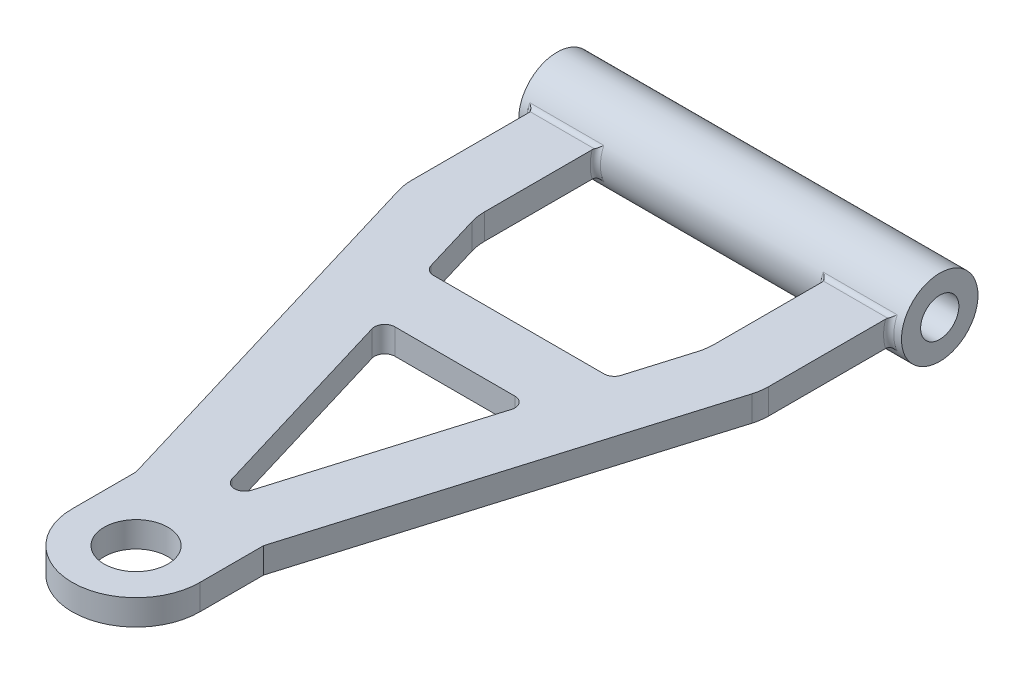
SolidWorks part; units mm, degrees
ref_plane "정면" through (0, 0, 0) normal (0, 0, 1) x (1, 0, 0)
ref_plane "윗면" through (0, 0, 0) normal (0, 1, 0) x (1, 0, 0)
ref_plane "우측면" through (0, 0, 0) normal (1, 0, 0) x (0, 0, -1)
sketch "스케치1" plane through (0, 0, 0) normal (1, 0, 0) x (0, 0, -1)
  circle A0 centre (0, 0) radius 7.5
  circle A1 centre (0, 0) radius 15
  dimension "D1" = 30
  dimension "D2" = 15
extrude "보스-돌출1" add sketch "스케치1" along normal mid plane 150
sketch "스케치2" plane through (0, 0, 0) normal (0, 1, 0) x (1, 0, 0)
  line L0 (-75, 0) -> (75, 0) construction
  line L1 (-75, 15) -> (-75, -15) construction
  line L2 (75, -15) -> (75, 15) construction
  line L3 (-70, 0) -> (-70, -65) construction
  line L4 (-70, -65) -> (-25, -215)
  line L5 (-25, -215) -> (-25, -240)
  line L6 (-25, -240) -> (25, -240) construction
  line L7 (25, -240) -> (25, -215)
  line L8 (25, -215) -> (70, -65)
  line L9 (70, -65) -> (70, 0) construction
  line L10 (-70, -65) -> (-70, -12)
  line L11 (-70, -12) -> (-45, -12)
  line L12 (70, -12) -> (70, -65)
  line L13 (-75, -15) -> (75, -15) construction
  line L14 (-45, -61.3308) -> (-45, -12)
  line L15 (-45, -61.3308) -> (-36.3992, -90)
  line L16 (3.8313, -198.5598) -> (28.8992, -115)
  line L17 (45, -12) -> (45, -61.3308)
  line L18 (-36.3992, -90) -> (36.3992, -90)
  line L19 (-28.8992, -115) -> (28.8992, -115)
  line L20 (36.3992, -90) -> (45, -61.3308)
  line L21 (-36.3992, -115) -> (36.3992, -115) construction
  line L22 (-28.8992, -115) -> (-3.8313, -198.5598)
  line L23 (1.0543, -207.8163) -> (45, -61.3308) construction
  line L24 (45, -12) -> (70, -12)
  line L25 (-45, -61.3308) -> (-1.0543, -207.8163) construction
  arc A0 (-25, -240) -> (25, -240) centre (0, -240) ccw
  arc A1 (-3.8313, -198.5598) -> (3.8313, -198.5598) centre (0, -197.4104) ccw
  circle A2 centre (0, -240) radius 12.5
  point P18 (0, -240)
  dimension "D4" = 50
  dimension "D9" = 8
  dimension "D12" = 25
  dimension "D1" = 240
  dimension "D2" = 140
  dimension "D3" = 70
  dimension "D5" = 65
  dimension "D6" = 25
  dimension "D7" = 3
  dimension "D11" = 25
  dimension "D8" = 25
  dimension "D10" = 25
extrude "보스-돌출2" add sketch "스케치2" along normal mid plane 10
fillet "필렛1" radius 4 4 edges at (36.3992, 0, 90) (-36.3992, 0, 90) (28.8992, 0, 115) (-28.8992, 0, 115)
fillet "필렛2" radius 20 4 edges at (-70, 0, 65) (45, 0, 61.3308) (-45, 0, 61.3308) (70, 0, 65)
fillet "필렛3" radius 2 8 edges at (-70, 0, 15) (-57.5, -5, 14.1421) (45, 0, 15) (57.5, -5, 14.1421) (57.5, 5, 14.1421) (70, 0, 15) (-45, 0, 15) (-57.5, 5, 14.1421)
